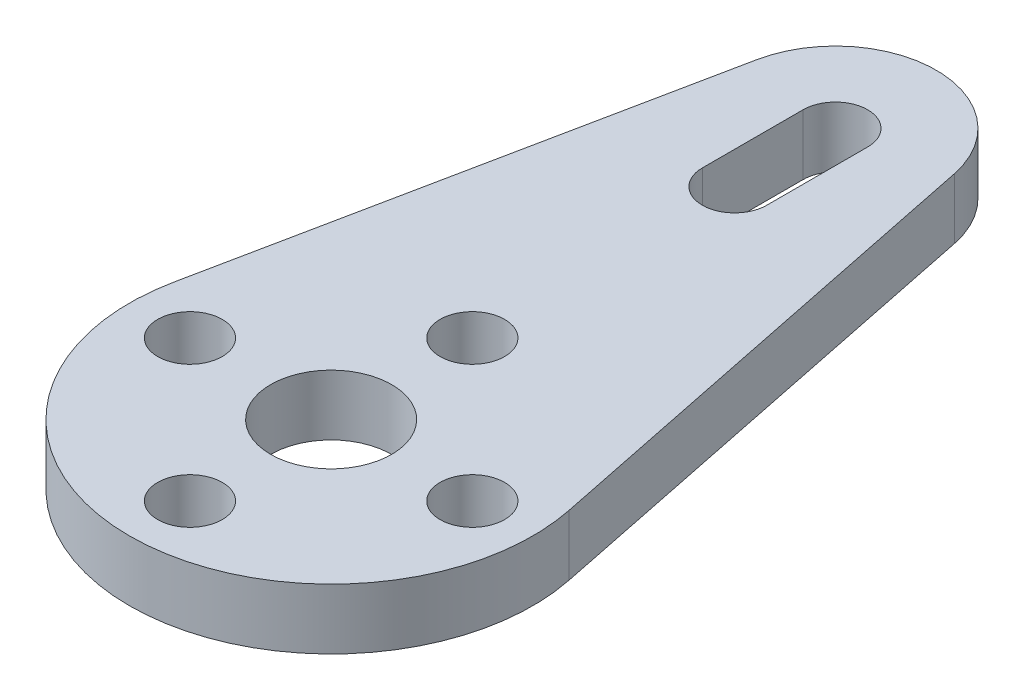
SolidWorks part; units mm, degrees
ref_plane "Front Plane" through (0, 0, 0) normal (0, 0, 1) x (1, 0, 0)
ref_plane "Top Plane" through (0, 0, 0) normal (0, 1, 0) x (1, 0, 0)
ref_plane "Right Plane" through (0, 0, 0) normal (1, 0, 0) x (0, 0, -1)
sketch "Sketch1" plane through (0, 0, 0) normal (0, 1, 0) x (1, 0, 0)
  line L0 (-4.899, 26) -> (-9.798, 2)
  line L1 (0, 25) -> (0, 0) construction
  line L2 (4.899, 26) -> (9.798, 2)
  line L3 (0, 25) -> (0, 20) construction
  line L4 (1.6, 25) -> (1.6, 20)
  line L5 (-1.6, 25) -> (-1.6, 20)
  arc A0 (-9.798, 2) -> (9.798, 2) centre (0, 0) ccw
  circle A1 centre (0, 0) radius 3
  circle A2 centre (0, 7) radius 1.6
  circle A3 centre (0, 0) radius 7 construction
  circle A4 centre (7, 0) radius 1.6
  circle A5 centre (0, -7) radius 1.6
  circle A6 centre (-7, 0) radius 1.6
  arc A7 (4.899, 26) -> (-4.899, 26) centre (0, 25) ccw
  arc A8 (1.6, 25) -> (-1.6, 25) centre (0, 25) ccw
  arc A9 (-1.6, 20) -> (1.6, 20) centre (0, 20) ccw
  point P1 (0, 22.5)
  point P16 (0, 0)
  dimension "D1" = 20
  dimension "D2" = 6
  dimension "D3" = 3.2
  dimension "D4" = 14
  dimension "D6" = 10
  dimension "D8" = 1.6
  dimension "D5" = 4
  dimension "D7" = 25
  dimension "D9" = 5
extrude "Boss-Extrude1" add sketch "Sketch1" along normal blind 3
